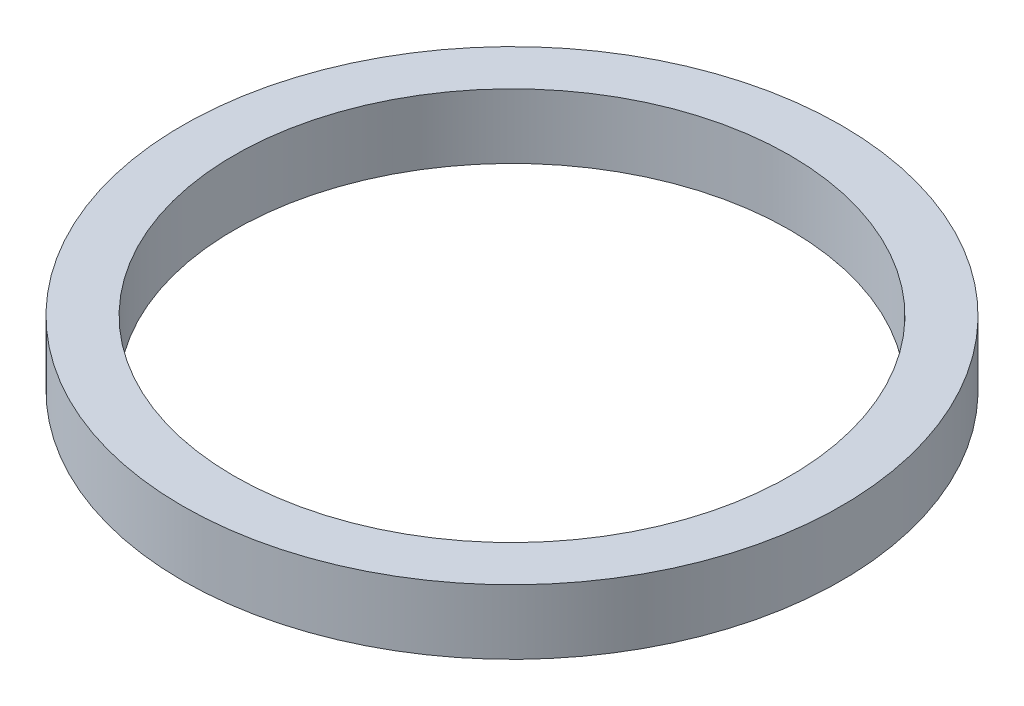
SolidWorks part; units mm, degrees
ref_plane "Alzado" through (0, 0, 0) normal (0, 0, 1) x (1, 0, 0)
ref_plane "Planta" through (0, 0, 0) normal (0, 1, 0) x (1, 0, 0)
ref_plane "Vista lateral" through (0, 0, 0) normal (1, 0, 0) x (0, 0, -1)
sketch "Croquis1" plane through (0, 0, 0) normal (0, 1, 0) x (1, 0, 0)
  circle A0 centre (0, 0) radius 21.5
  circle A1 centre (0, 0) radius 25.5
  dimension "D1" = 43
  dimension "D2" = 4
extrude "Saliente-Extruir1" add sketch "Croquis1" along normal blind 5
